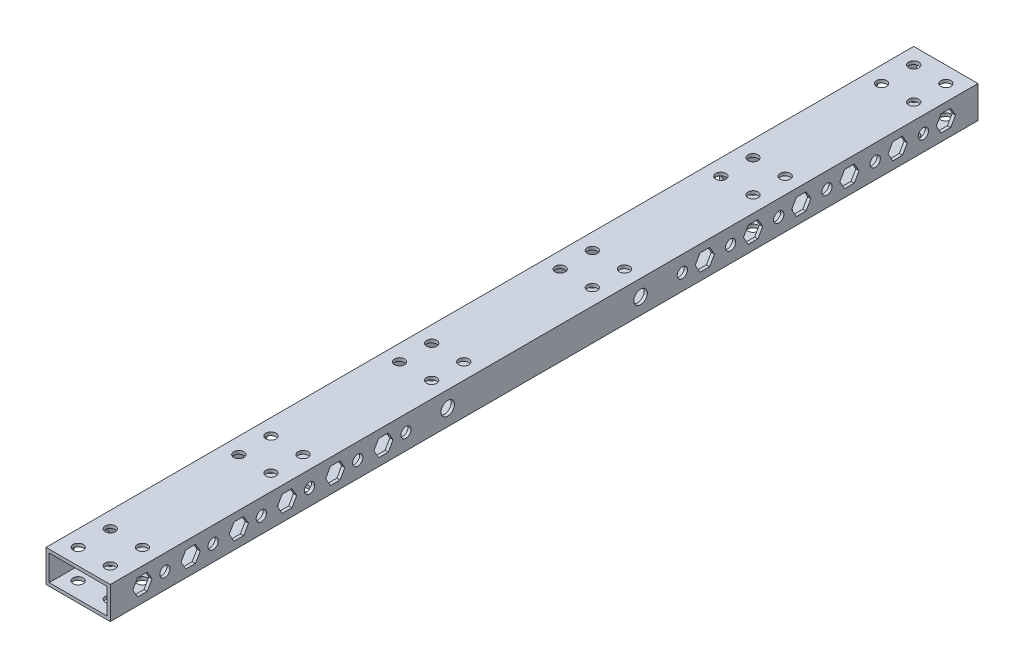
SolidWorks part; units mm, degrees
ref_plane "前视基准面" through (0, 0, 0) normal (0, 0, 1) x (1, 0, 0)
ref_plane "上视基准面" through (0, 0, 0) normal (0, 1, 0) x (1, 0, 0)
ref_plane "右视基准面" through (0, 0, 0) normal (1, 0, 0) x (0, 0, -1)
other "Configuration Table"
sketch "草图1" plane through (0, 0, 0) normal (0, 0, 1) x (1, 0, 0)
  line L1 (0, 0) -> (20, 0)
  line L2 (0, 0) -> (0, -10)
  line L3 (0, -10) -> (20, -10)
  line L4 (20, 0) -> (20, -10)
  dimension "D1" = 20
  dimension "D2" = 10
extrude "拉伸-薄壁1" add sketch "草图1" along normal blind 270 thin
sketch "草图2" plane through (0, 0, 0) normal (0, 1, 0) x (1, 0, 0)
  line L0 (0, -135) -> (20, -135) construction
  line L1 (0, -270) -> (0, 0) construction
  line L2 (20, -270) -> (20, 0) construction
  line L3 (0, -10) -> (20, -10) construction
  line L4 (10, 0) -> (10, -10) construction
  line L5 (20, 0) -> (0, 0) construction
  line L6 (10, -270) -> (10, -260) construction
  line L7 (0, -260) -> (20, -260) construction
  circle A0 centre (5, -5) radius 1.575
  circle A1 centre (15, -5) radius 1.575
  circle A2 centre (15, -15) radius 1.575
  circle A3 centre (5, -15) radius 1.575
  circle A4 centre (5, -255) radius 1.575
  circle A5 centre (15, -255) radius 1.575
  circle A6 centre (15, -265) radius 1.575
  circle A7 centre (5, -265) radius 1.575
  circle A8 centre (5, -55) radius 1.575
  circle A9 centre (15, -55) radius 1.575
  circle A10 centre (5, -65) radius 1.575
  circle A11 centre (15, -65) radius 1.575
  circle A12 centre (5, -105) radius 1.575
  circle A13 centre (15, -105) radius 1.575
  circle A14 centre (5, -115) radius 1.575
  circle A15 centre (15, -115) radius 1.575
  circle A16 centre (15, -155) radius 1.575
  circle A17 centre (5, -155) radius 1.575
  circle A18 centre (15, -165) radius 1.575
  circle A19 centre (5, -165) radius 1.575
  circle A20 centre (15, -205) radius 1.575
  circle A21 centre (5, -205) radius 1.575
  circle A22 centre (15, -215) radius 1.575
  circle A23 centre (5, -215) radius 1.575
  dimension "D2" = 3.15
  dimension "D1" = 10
  dimension "D3" = 5
  dimension "D4" = 5
  dimension "D5" = 50
extrude "切除-拉伸1" cut sketch "草图2" against normal through all
sketch "草图3" plane through (0, 0, 0) normal (-1, 0, 0) x (0, 0, 1)
  line L0 (135, 0) -> (135, -10) construction
  line L1 (270, 0) -> (0, 0) construction
  line L2 (270, -10) -> (0, -10) construction
  line L3 (105, -5) -> (0, -5) construction
  line L4 (8.5, -7.5981) -> (11.5, -7.5981)
  line L5 (11.5, -7.5981) -> (13, -5)
  line L6 (13, -5) -> (11.5, -2.4019)
  line L7 (11.5, -2.4019) -> (8.5, -2.4019)
  line L8 (8.5, -2.4019) -> (7, -5)
  line L9 (7, -5) -> (8.5, -7.5981)
  line L10 (26.5, -2.4019) -> (23.5, -2.4019)
  line L11 (28, -5) -> (26.5, -2.4019)
  line L12 (0, 0) -> (0, -10) construction
  line L13 (26.5, -7.5981) -> (28, -5)
  line L14 (23.5, -7.5981) -> (26.5, -7.5981)
  line L15 (22, -5) -> (23.5, -7.5981)
  line L16 (23.5, -2.4019) -> (22, -5)
  line L17 (41.5, -2.4019) -> (38.5, -2.4019)
  line L18 (43, -5) -> (41.5, -2.4019)
  line L19 (41.5, -7.5981) -> (43, -5)
  line L20 (38.5, -7.5981) -> (41.5, -7.5981)
  line L21 (37, -5) -> (38.5, -7.5981)
  line L22 (38.5, -2.4019) -> (37, -5)
  line L23 (56.5, -2.4019) -> (53.5, -2.4019)
  line L24 (58, -5) -> (56.5, -2.4019)
  line L25 (56.5, -7.5981) -> (58, -5)
  line L26 (53.5, -7.5981) -> (56.5, -7.5981)
  line L27 (52, -5) -> (53.5, -7.5981)
  line L28 (53.5, -2.4019) -> (52, -5)
  line L29 (71.5, -2.4019) -> (68.5, -2.4019)
  line L30 (73, -5) -> (71.5, -2.4019)
  line L31 (71.5, -7.5981) -> (73, -5)
  line L32 (68.5, -7.5981) -> (71.5, -7.5981)
  line L33 (67, -5) -> (68.5, -7.5981)
  line L34 (68.5, -2.4019) -> (67, -5)
  line L35 (86.5, -2.4019) -> (83.5, -2.4019)
  line L36 (88, -5) -> (86.5, -2.4019)
  line L37 (86.5, -7.5981) -> (88, -5)
  line L38 (83.5, -7.5981) -> (86.5, -7.5981)
  line L39 (82, -5) -> (83.5, -7.5981)
  line L40 (83.5, -2.4019) -> (82, -5)
  line L41 (186.5, -2.4019) -> (188, -5)
  line L42 (188, -5) -> (186.5, -7.5981)
  line L43 (186.5, -7.5981) -> (183.5, -7.5981)
  line L44 (183.5, -7.5981) -> (182, -5)
  line L45 (182, -5) -> (183.5, -2.4019)
  line L46 (183.5, -2.4019) -> (186.5, -2.4019)
  line L47 (201.5, -2.4019) -> (203, -5)
  line L48 (203, -5) -> (201.5, -7.5981)
  line L49 (201.5, -7.5981) -> (198.5, -7.5981)
  line L50 (198.5, -7.5981) -> (197, -5)
  line L51 (197, -5) -> (198.5, -2.4019)
  line L52 (198.5, -2.4019) -> (201.5, -2.4019)
  line L53 (216.5, -2.4019) -> (218, -5)
  line L54 (218, -5) -> (216.5, -7.5981)
  line L55 (216.5, -7.5981) -> (213.5, -7.5981)
  line L56 (213.5, -7.5981) -> (212, -5)
  line L57 (212, -5) -> (213.5, -2.4019)
  line L58 (213.5, -2.4019) -> (216.5, -2.4019)
  line L59 (231.5, -2.4019) -> (233, -5)
  line L60 (233, -5) -> (231.5, -7.5981)
  line L61 (231.5, -7.5981) -> (228.5, -7.5981)
  line L62 (228.5, -7.5981) -> (227, -5)
  line L63 (227, -5) -> (228.5, -2.4019)
  line L64 (228.5, -2.4019) -> (231.5, -2.4019)
  line L65 (246.5, -2.4019) -> (248, -5)
  line L66 (248, -5) -> (246.5, -7.5981)
  line L67 (246.5, -7.5981) -> (243.5, -7.5981)
  line L68 (243.5, -7.5981) -> (242, -5)
  line L69 (242, -5) -> (243.5, -2.4019)
  line L70 (243.5, -2.4019) -> (246.5, -2.4019)
  line L71 (263, -5) -> (261.5, -7.5981)
  line L72 (261.5, -2.4019) -> (263, -5)
  line L73 (258.5, -2.4019) -> (261.5, -2.4019)
  line L74 (257, -5) -> (258.5, -2.4019)
  line L75 (258.5, -7.5981) -> (257, -5)
  line L76 (261.5, -7.5981) -> (258.5, -7.5981)
  circle A1 centre (105, -5) radius 2.1
  circle A4 centre (165, -5) radius 2.1
  circle A5 centre (10, -5) radius 2.5981 construction
  circle A6 centre (17, -5) radius 1.6
  circle A7 centre (32, -5) radius 1.6
  circle A8 centre (25, -5) radius 2.5981 construction
  circle A9 centre (47, -5) radius 1.6
  circle A10 centre (40, -5) radius 2.5981 construction
  circle A11 centre (62, -5) radius 1.6
  circle A12 centre (55, -5) radius 2.5981 construction
  circle A13 centre (77, -5) radius 1.6
  circle A14 centre (70, -5) radius 2.5981 construction
  circle A15 centre (92, -5) radius 1.6
  circle A16 centre (85, -5) radius 2.5981 construction
  circle A17 centre (185, -5) radius 2.5981 construction
  circle A18 centre (200, -5) radius 2.5981 construction
  circle A19 centre (215, -5) radius 2.5981 construction
  circle A20 centre (230, -5) radius 2.5981 construction
  circle A21 centre (245, -5) radius 2.5981 construction
  circle A22 centre (260, -5) radius 2.5981 construction
  circle A23 centre (178, -5) radius 1.6
  circle A24 centre (193, -5) radius 1.6
  circle A25 centre (208, -5) radius 1.6
  circle A26 centre (223, -5) radius 1.6
  circle A27 centre (238, -5) radius 1.6
  circle A28 centre (253, -5) radius 1.6
  dimension "D4" = 3
  dimension "D2" = 4.2
  dimension "D6" = 3.2
  dimension "D1" = 30
  dimension "D3" = 5
  dimension "D5" = 10
  dimension "D7" = 7
  dimension "D8" = 15
extrude "切除-拉伸2" cut sketch "草图3" against normal through all
